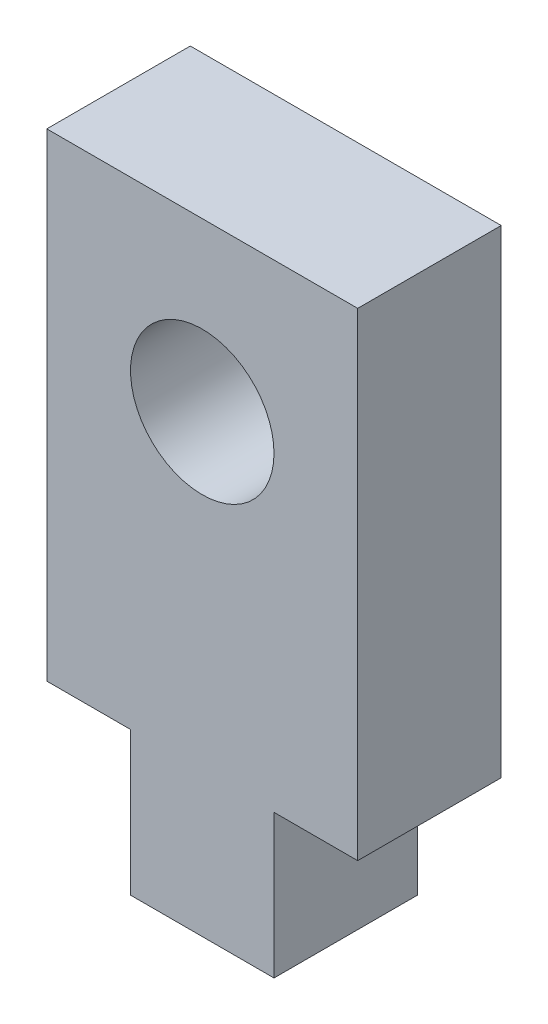
SolidWorks part; units mm, degrees
ref_plane "Alzado" through (0, 0, 0) normal (0, 0, 1) x (1, 0, 0)
ref_plane "Planta" through (0, 0, 0) normal (0, 1, 0) x (1, 0, 0)
ref_plane "Vista lateral" through (0, 0, 0) normal (1, 0, 0) x (0, 0, -1)
sketch "Croquis2" plane through (0, 0, 0) normal (0, 0, 1) x (1, 0, 0)
  line L0 (-3.25, -5) -> (-3.25, 5)
  line L1 (-3.25, -5) -> (-1.5, -5)
  line L2 (-3.25, 5) -> (3.25, 5)
  line L3 (3.25, -5) -> (3.25, 5)
  line L4 (-3.25, -5) -> (3.25, 5) construction
  line L5 (-3.25, 5) -> (3.25, -5) construction
  line L6 (-1.5, -8) -> (-1.5, -5)
  line L7 (-1.5, -8) -> (1.5, -8)
  line L9 (1.5, -8) -> (1.5, -5)
  line L10 (-1.5, -8) -> (1.5, -5) construction
  line L11 (-1.5, -5) -> (1.5, -8) construction
  line L12 (1.5, -5) -> (3.25, -5)
  circle A0 centre (0, 1.5) radius 1.5
  point P1 (0, 0)
  point P3 (0, 0)
  point P9 (0, -6.5)
  point P10 (0, 0)
  point P11 (0, 0)
  dimension "D3" = 3
  dimension "D1" = 10
  dimension "D2" = 6.5
  dimension "D4" = 3
  dimension "D5" = 3
  dimension "D6" = 6.5
extrude "Saliente-Extruir1" add sketch "Croquis2" along normal blind 3
